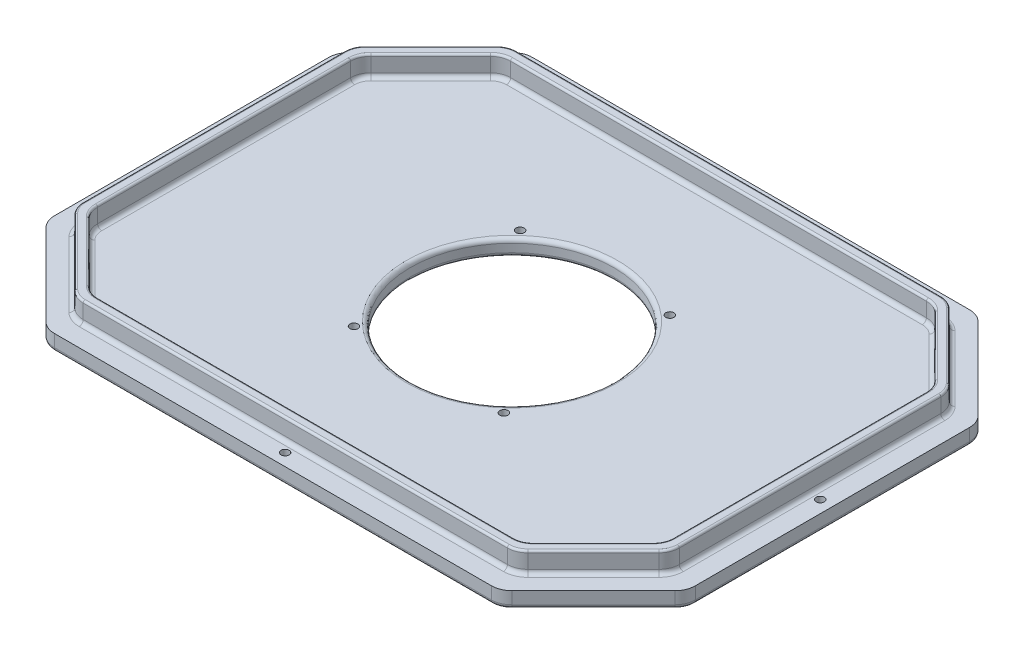
SolidWorks part; units mm, degrees
material "ABS"
ref_plane "Front Plane" through (0, 0, 0) normal (0, 0, 1) x (1, 0, 0)
ref_plane "Top Plane" through (0, 0, 0) normal (0, 1, 0) x (1, 0, 0)
ref_plane "Right Plane" through (0, 0, 0) normal (1, 0, 0) x (0, 0, -1)
sketch "Sketch1" plane through (0, 0, 0) normal (0, 1, 0) x (1, 0, 0)
  line L0 (111.5381, -117.5) -> (157.5, -71.5381)
  line L1 (-55, 0) -> (55, 0) construction
  line L2 (-146.5, -68.3959) -> (-146.5, 68.3959)
  line L3 (-146.5, -106.5) -> (-108.3959, -106.5) construction
  line L4 (146.5, -68.3959) -> (146.5, 68.3959)
  line L5 (-146.5, -106.5) -> (146.5, 106.5) construction
  line L6 (-146.5, 106.5) -> (146.5, -106.5) construction
  line L7 (-111.5381, -117.5) -> (111.5381, -117.5)
  line L8 (-157.5, -71.5381) -> (-157.5, 71.5381)
  line L9 (-111.5381, 117.5) -> (111.5381, 117.5)
  line L10 (157.5, -71.5381) -> (157.5, 71.5381)
  line L11 (-157.5, -117.5) -> (157.5, 117.5) construction
  line L12 (-157.5, 117.5) -> (157.5, -117.5) construction
  line L14 (111.5381, -117.5) -> (157.5, -117.5) construction
  line L15 (157.5, -117.5) -> (157.5, -71.5381) construction
  line L16 (146.5, -106.5) -> (146.5, -68.3959) construction
  line L17 (108.3959, 106.5) -> (146.5, 68.3959)
  line L18 (111.5381, 117.5) -> (157.5, 71.5381)
  line L20 (108.3959, -106.5) -> (146.5, -106.5) construction
  line L21 (108.3959, -106.5) -> (146.5, -68.3959)
  line L22 (108.3959, 106.5) -> (146.5, 106.5) construction
  line L29 (111.5381, 117.5) -> (157.5, 117.5) construction
  line L30 (157.5, 71.5381) -> (157.5, 117.5) construction
  line L31 (146.5, 106.5) -> (146.5, 68.3959) construction
  line L32 (0, -55) -> (0, 55) construction
  line L33 (-111.5381, -117.5) -> (-157.5, -71.5381)
  line L34 (-108.3959, -106.5) -> (-146.5, -68.3959)
  line L35 (-111.5381, 117.5) -> (-157.5, 71.5381)
  line L36 (-157.5, 117.5) -> (-111.5381, 117.5) construction
  line L37 (-157.5, 71.5381) -> (-157.5, 117.5) construction
  line L38 (-146.5, 68.3959) -> (-146.5, 106.5) construction
  line L39 (-108.3959, 106.5) -> (-146.5, 68.3959)
  line L40 (-108.3959, 106.5) -> (108.3959, 106.5)
  line L41 (-146.5, 106.5) -> (-108.3959, 106.5) construction
  line L43 (-146.5, -106.5) -> (-146.5, -68.3959) construction
  line L45 (-108.3959, -106.5) -> (108.3959, -106.5)
  line L48 (-157.5, -117.5) -> (-157.5, -71.5381) construction
  line L49 (-157.5, -117.5) -> (-111.5381, -117.5) construction
  line L51 (104.467, -110.4289) -> (150.4289, -64.467) construction
  point P0 (0, 0)
  point P5 (0, 0)
  dimension "D1" = 293
  dimension "D2" = 213
  dimension "D3" = 235
  dimension "D4" = 315
  dimension "D5" = 65
  dimension "D6" = 45
  dimension "D7" = 10
extrude "Boss-Extrude1" add sketch "Sketch1" along normal mid plane 8 contours L34 L45 L21 L4 L17 L40 L39 L2 | L9 L35 L8 L33 L7 L0 L10 L18 L45 L34 L2 L39 L40 L17 L4 L21
sketch "Sketch2" plane through (0, 4, 0) normal (0, 1, 0) x (1, 0, 0)
  line L0 (108.3959, 106.5) -> (146.5, 68.3959) construction
  line L1 (146.5, -68.3959) -> (146.5, 68.3959) construction
  line L2 (108.3959, -106.5) -> (146.5, -68.3959) construction
  line L3 (-108.3959, -106.5) -> (108.3959, -106.5) construction
  line L4 (-108.3959, -106.5) -> (-146.5, -68.3959) construction
  line L5 (-146.5, -68.3959) -> (-146.5, 68.3959) construction
  line L6 (-108.3959, 106.5) -> (108.3959, 106.5) construction
  line L7 (-108.3959, 106.5) -> (-146.5, 68.3959) construction
  line L8 (108.3959, 106.5) -> (146.5, 68.3959)
  line L9 (146.5, -68.3959) -> (146.5, 68.3959)
  line L10 (108.3959, -106.5) -> (146.5, -68.3959)
  line L11 (-108.3959, -106.5) -> (108.3959, -106.5)
  line L12 (-108.3959, -106.5) -> (-146.5, -68.3959)
  line L13 (-146.5, -68.3959) -> (-146.5, 68.3959)
  line L14 (-108.3959, 106.5) -> (108.3959, 106.5)
  line L15 (-108.3959, 106.5) -> (-146.5, 68.3959)
  line L16 (106.3249, 101.5) -> (141.5, 66.3249)
  line L17 (141.5, -66.3249) -> (141.5, 66.3249)
  line L18 (106.3249, -101.5) -> (141.5, -66.3249)
  line L19 (-106.3249, -101.5) -> (106.3249, -101.5)
  line L20 (-106.3249, -101.5) -> (-141.5, -66.3249)
  line L21 (-141.5, -66.3249) -> (-141.5, 66.3249)
  line L22 (-106.3249, 101.5) -> (-141.5, 66.3249)
  line L23 (-106.3249, 101.5) -> (106.3249, 101.5)
  dimension "D1" = 5
extrude "Boss-Extrude2" add sketch "Sketch2" along normal blind 10
sketch "Sketch3" plane through (0, 4, 0) normal (0, 1, 0) x (1, 0, 0)
  line L0 (108.3959, 106.5) -> (-108.3959, 106.5) construction
  line L1 (-108.3959, -106.5) -> (108.3959, -106.5) construction
  line L2 (146.5, -68.3959) -> (146.5, 68.3959) construction
  line L3 (-146.5, 68.3959) -> (-146.5, -68.3959) construction
  circle A0 centre (0, 111.5) radius 2
  circle A1 centre (0, -111.5) radius 2
  circle A2 centre (151.5, 0) radius 2
  circle A3 centre (-151.5, 0) radius 2
  dimension "D1" = 4
  dimension "D2" = 5
  dimension "D3" = 5
  dimension "D4" = 5
  dimension "D5" = 5
extrude "Cut-Extrude1" cut sketch "Sketch3" against normal through all both and the other way through all
sketch "Sketch4" plane through (0, -4, 0) normal (0, -1, 0) x (1, 0, 0)
  circle A0 centre (0, 0) radius 50
  circle A1 centre (36, -41.5812) radius 3 construction
  circle A2 centre (0, 0) radius 55 construction
  circle A3 centre (-36.842, 40.8371) radius 2
  circle A4 centre (36.842, 40.8371) radius 2
  circle A5 centre (-36.842, -40.8371) radius 2
  circle A6 centre (36, -41.5812) radius 2
  point P8 (-36.842, -40.8371)
  point P9 (36.842, 40.8371)
  point P10 (-36.842, 40.8371)
  point P11 (36, -41.5812)
  dimension "D1" = 100
  dimension "D2" = 110
  dimension "D3" = 6
  dimension "D8" = 4
  dimension "D9" = 4
  dimension "D10" = 4
  dimension "D4" = 36
  dimension "D5" = 81.6742
  dimension "D6" = 36.842
  dimension "D7" = 36.842
extrude "Cut-Extrude2" cut sketch "Sketch4" against normal through all both contours A5 | A6 | A3 | A4 | A0
fillet "Fillet1" radius 10 24 edges at (108.3959, 9, 106.5) (146.5, 9, 68.3959) (146.5, 9, -68.3959) (108.3959, 9, -106.5) (-108.3959, 9, -106.5) (-146.5, 9, -68.3959) (-146.5, 9, 68.3959) (-108.3959, 9, 106.5) (111.5381, 0, 117.5) (157.5, 0, 71.5381) (-111.5381, 0, 117.5) (-157.5, 0, 71.5381) (-157.5, 0, -71.5381) (-111.5381, 0, -117.5) (157.5, 0, -71.5381) (111.5381, 0, -117.5) (141.5, 9, -66.3249) (106.3249, 9, -101.5) (106.3249, 9, 101.5) (141.5, 9, 66.3249) (-141.5, 9, 66.3249) (-106.3249, 9, 101.5) (-106.3249, 9, -101.5) (-141.5, 9, -66.3249)
fillet "Fillet3" radius 2 32 edges at (106.0096, 4, -100.7388) (123.9124, 4, -83.9124) (140.7388, 4, -66.0096) (141.5, 4, 0) (140.7388, 4, 66.0096) (123.9124, 4, 83.9124) (106.0096, 4, 100.7388) (0, 4, 101.5) (-106.0096, 4, 100.7388) (-123.9124, 4, 83.9124) (-140.7388, 4, 66.0096) (-141.5, 4, 0) (-140.7388, 4, -66.0096) (-123.9124, 4, -83.9124) (-106.0096, 4, -100.7388) (-108.0806, 4, 105.7388) (-127.448, 4, 87.448) (-145.7388, 4, 68.0806) (-146.5, 4, 0) (-145.7388, 4, -68.0806) (-127.448, 4, -87.448) (-108.0806, 4, -105.7388) (0, 4, -106.5) (108.0806, 4, -105.7388) (127.448, 4, -87.448) (145.7388, 4, -68.0806) (146.5, 4, 0) (145.7388, 4, 68.0806) (127.448, 4, 87.448) (108.0806, 4, 105.7388) (0, 4, -101.5) (0, 4, 106.5)
fillet "Fillet4" radius 1 32 edges at (-140.7388, 14, -66.0096) (-141.5, 14, 0) (-140.7388, 14, 66.0096) (-123.9124, 14, 83.9124) (-106.0096, 14, 100.7388) (0, 14, 101.5) (106.0096, 14, 100.7388) (123.9124, 14, 83.9124) (140.7388, 14, 66.0096) (141.5, 14, 0) (140.7388, 14, -66.0096) (123.9124, 14, -83.9124) (106.0096, 14, -100.7388) (0, 14, -101.5) (-106.0096, 14, -100.7388) (-123.9124, 14, -83.9124) (-108.0806, 14, 105.7388) (-127.448, 14, 87.448) (-145.7388, 14, 68.0806) (-146.5, 14, 0) (-145.7388, 14, -68.0806) (-127.448, 14, -87.448) (-108.0806, 14, -105.7388) (0, 14, -106.5) (108.0806, 14, -105.7388) (127.448, 14, -87.448) (145.7388, 14, -68.0806) (146.5, 14, 0) (145.7388, 14, 68.0806) (127.448, 14, 87.448) (108.0806, 14, 105.7388) (0, 14, 106.5)
fillet "Fillet6" radius 2 16 edges at (-111.2228, -4, 116.7388) (0, -4, 117.5) (111.2228, -4, 116.7388) (134.519, -4, 94.519) (156.7388, -4, 71.2228) (157.5, -4, 0) (156.7388, -4, -71.2228) (134.519, -4, -94.519) (111.2228, -4, -116.7388) (0, -4, -117.5) (-111.2228, -4, -116.7388) (-134.519, -4, -94.519) (-156.7388, -4, -71.2228) (-157.5, -4, 0) (-156.7388, -4, 71.2228) (-134.519, -4, 94.519)
fillet "Fillet7" radius 2 2 edges at (0, 4, 50) (0, -4, -50)
sketch "Sketch5" plane through (0, -4, 0) normal (0, -1, 0) x (1, 0, 0)
  line L0 (-157.5, -67.3959) -> (-157.5, 67.3959) construction
  line L1 (0, 82.5412) -> (0, -82.5412) construction
  line L52 (-70, 70) -> (70, 70) construction
  line L53 (-37.5, -93) -> (37.5, -93) construction
  line L55 (-150, -10) -> (-60, -10) construction
  line L56 (150, -10) -> (60, -10) construction
  line L57 (-50, 0) -> (50, 0) construction
  circle A0 centre (0, 0) radius 50 construction
  circle A1 centre (0, 0) radius 60.5 construction
  text T0 "LAM" font "Times New Roman" height 25
  text T1 "RC" font "Times New Roman" height 25
  text T2 "T-WORKS" font "Times New Roman" height 20
  text T3 "2025" font "Times New Roman" height 23
  point P4 (0, 70)
  point P5 (0, 0)
  point P60 (0, -93)
  dimension "D1" = 121
  dimension "D3" = 93
  dimension "D4" = 10
  dimension "D5" = 90
  dimension "D6" = 7.5
  dimension "D20" = 140
  dimension "D22" = 75
  dimension "65" = 70
extrude "Cut-Extrude3" [suppressed] cut sketch "Sketch5" against normal blind 5
